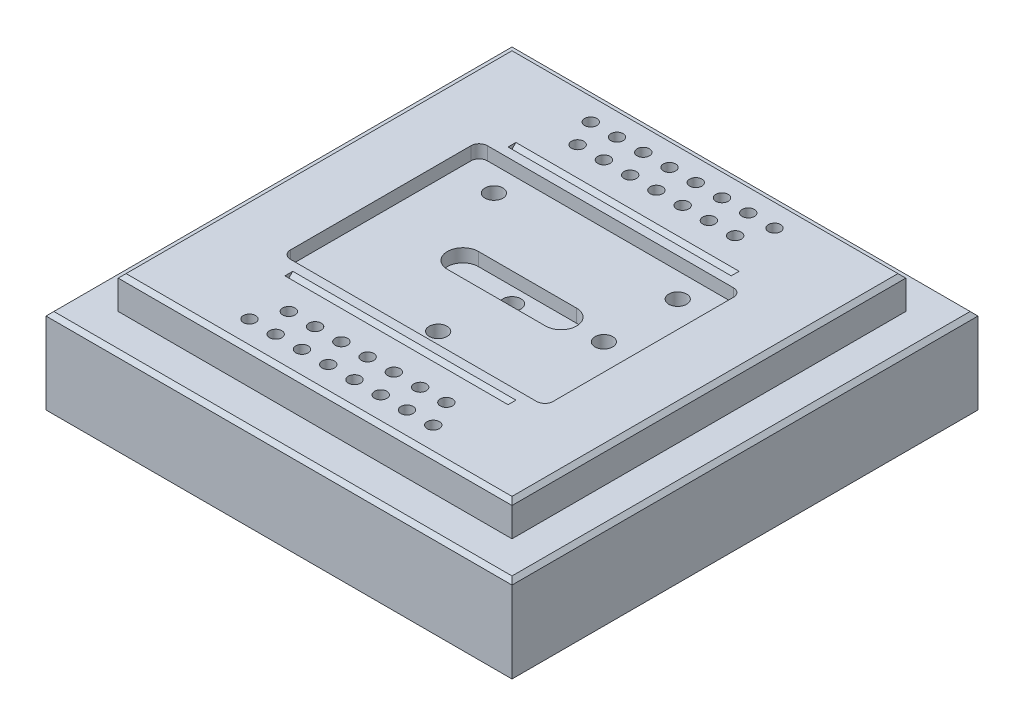
SolidWorks part; units mm, degrees
material "Acrylic (Medium-high impact)"
ref_plane "Front Plane" through (0, 0, 0) normal (0, 0, 1) x (1, 0, 0)
ref_plane "Top Plane" through (0, 0, 0) normal (0, 1, 0) x (1, 0, 0)
ref_plane "Right Plane" through (0, 0, 0) normal (1, 0, 0) x (0, 0, -1)
sketch "Sketch1" plane through (0, 0, 0) normal (0, 1, 0) x (1, 0, 0)
  line L1 (-38.1, 38.1) -> (38.1, 38.1)
  line L2 (-38.1, 38.1) -> (-38.1, -38.1)
  line L3 (-38.1, -38.1) -> (38.1, -38.1)
  line L4 (38.1, 38.1) -> (38.1, -38.1)
  line L5 (-38.1, 38.1) -> (38.1, -38.1) construction
  line L6 (-38.1, -38.1) -> (38.1, 38.1) construction
  point P0 (0, 0)
  dimension "D1" = 76.2
  dimension "D2" = 76.2
extrude "Boss-Extrude1" add sketch "Sketch1" along normal blind 6.35 contours L1 L4 L3 L2
sketch "Sketch13" plane through (0, 0, 0) normal (0, -1, 0) x (1, 0, 0)
  line L1 (-45.085, 45.085) -> (45.085, 45.085)
  line L2 (-45.085, 45.085) -> (-45.085, -45.085)
  line L3 (-45.085, -45.085) -> (45.085, -45.085)
  line L4 (45.085, 45.085) -> (45.085, -45.085)
  line L5 (-45.085, 45.085) -> (45.085, -45.085) construction
  line L6 (-45.085, -45.085) -> (45.085, 45.085) construction
  point P0 (0, 0)
  dimension "D1" = 90.17
  dimension "D2" = 90.17
extrude "Boss-Extrude2" add sketch "Sketch13" along normal blind 16.51
sketch "Sketch2" plane through (0, 6.35, 0) normal (0, 1, 0) x (1, 0, 0)
  line L1 (-23.8125, 19.05) -> (23.8125, 19.05)
  line L2 (-25.4, 17.4625) -> (-25.4, -17.4625)
  line L3 (-23.8125, -19.05) -> (23.8125, -19.05)
  line L4 (25.4, 17.4625) -> (25.4, -17.4625)
  line L5 (-25.4, 19.05) -> (25.4, -19.05) construction
  line L6 (-25.4, -19.05) -> (25.4, 19.05) construction
  arc A0 (-25.4, -17.4625) -> (-23.8125, -19.05) centre (-23.8125, -17.4625) ccw
  arc A1 (23.8125, -19.05) -> (25.4, -17.4625) centre (23.8125, -17.4625) ccw
  arc A2 (23.8125, 19.05) -> (25.4, 17.4625) centre (23.8125, 17.4625) cw
  arc A3 (-23.8125, 19.05) -> (-25.4, 17.4625) centre (-23.8125, 17.4625) ccw
  point P0 (0, 0)
  dimension "D3" = 1.5875
  dimension "D1" = 38.1
  dimension "D2" = 50.8
extrude "Cut-Extrude1" cut sketch "Sketch2" against normal blind 2.54
hole_wizard "3/32 (0.09375) Diameter Hole1" positions "Sketch7" profile "Sketch6" hole size "3/32" standard "ANSI Inch"
sketch "Sketch7" plane through (0, 6.35, 0) normal (0, 1, 0) x (1, 0, 0)
  line L0 (0, 0) -> (0, 38.1) construction
  line L2 (-15.24, 27.94) -> (15.24, 27.94) construction
  line L3 (-38.1, 38.1) -> (38.1, 38.1) construction
  line L4 (-17.78, 33.02) -> (17.78, 33.02) construction
  point P6 (-15.24, 27.94)
  point P7 (15.24, 27.94)
  point P17 (0, 27.94)
  point P18 (-17.78, 33.02)
  point P19 (17.78, 33.02)
  point P30 (-12.7, 33.02)
  point P31 (-7.62, 33.02)
  point P32 (-2.54, 33.02)
  point P33 (2.54, 33.02)
  point P34 (7.62, 33.02)
  point P35 (12.7, 33.02)
  point P36 (17.78, 33.02)
  point P38 (0, 33.02)
  point P53 (-10.16, 27.94)
  point P54 (-5.08, 27.94)
  point P55 (0, 27.94)
  point P56 (5.08, 27.94)
  point P57 (10.16, 27.94)
  point P58 (15.24, 27.94)
  dimension "D1" = 30.48
  dimension "D2" = 5.08
  dimension "D3" = 27.94
  dimension "D4" = 35.56
  dimension "D5" = 8
  dimension "D6" = 7
sketch "Sketch6" plane through (-15.24, 6.35, -27.94) normal (1, 0, 0) x (0, 0, 1)
  line L0 (0, 0) -> (0, 8.3354)
  line L1 (0, 8.3354) -> (1.1906, 7.62)
  line L2 (1.1906, 7.62) -> (1.1906, 0)
  line L5 (1.1906, 0) -> (0, 0)
  line L10 (0, 8.3354) -> (-1.1906, 7.62) construction
  line L11 (0, -6.35) -> (0, 107.95) construction
  dimension "Hole Dia." = 2.3812
  dimension "Hole Depth" = 7.62
  dimension "Drill Angle" = 118
mirror "Mirror1" about plane through (0, 0, 0) normal (0, 0, 1) of "3/32 (0.09375) Diameter Hole1"
sketch "Sketch8" plane through (0, 0, 0) normal (1, 0, 0) x (0, 0, -1)
  line L0 (20.828, 6.35) -> (21.59, 5.588)
  line L1 (-38.1, 6.35) -> (38.1, 6.35) construction
  line L2 (21.59, 5.588) -> (22.352, 6.35)
  line L3 (22.352, 6.35) -> (20.828, 6.35)
  line L4 (21.59, 6.35) -> (21.59, 5.588) construction
  dimension "D1" = 0.762
  dimension "D2" = 21.59
extrude "Cut-Extrude4" cut sketch "Sketch8" against normal mid plane 43.18
mirror "Mirror2" about plane through (0, 0, 0) normal (0, 0, 1) of "Cut-Extrude4"
chamfer "Chamfer1" distance 0.762 angle 45 8 edges at (-38.1, 6.35, 0) (0, 6.35, -38.1) (38.1, 6.35, 0) (0, 6.35, 38.1) (0, 0, -45.085) (-45.085, 0, 0) (0, 0, 45.085) (45.085, 0, 0)
hole_wizard "1/4 (0.25) Diameter Hole1" [suppressed] positions "Sketch10" profile "Sketch11" hole size "1/4" standard "ANSI Inch"
sketch "Sketch10" plane through (0, 6.35, 0) normal (0, 1, 0) x (1, 0, 0)
  line L0 (-31.75, 15.875) -> (-31.75, -15.875) construction
  line L2 (-31.75, 0) -> (0, 0) construction
  line L4 (-38.1, -38.1) -> (-38.1, 38.1) construction
  point P0 (-31.75, 15.875)
  point P2 (-31.75, -15.875)
  dimension "D1" = 31.75
  dimension "D2" = 6.35
sketch "Sketch11" plane through (-31.75, 6.35, -15.875) normal (1, 0, 0) x (0, 0, 1)
  line L0 (0, 0) -> (0, 18.4177)
  line L1 (0, 18.4177) -> (3.175, 16.51)
  line L2 (3.175, 16.51) -> (3.175, 0)
  line L5 (3.175, 0) -> (0, 0)
  line L10 (0, 18.4177) -> (-3.175, 16.51) construction
  line L11 (0, -6.35) -> (0, 107.95) construction
  dimension "Hole Dia." = 6.35
  dimension "Hole Depth" = 16.51
  dimension "Drill Angle" = 118
sketch "Sketch14" plane through (0, -16.51, 0) normal (0, -1, 0) x (1, 0, 0)
  line L0 (-38.735, 34.925) -> (31.115, 34.925)
  line L1 (34.29, 31.75) -> (34.29, -31.75)
  line L2 (31.115, -34.925) -> (-38.735, -34.925)
  line L3 (-41.91, -31.75) -> (-41.91, -15.875)
  line L4 (-38.735, -12.7) -> (-25.4, -12.7)
  line L5 (-22.86, -10.16) -> (-22.86, 10.16)
  line L6 (-25.4, 12.7) -> (-38.735, 12.7)
  line L7 (-41.91, 15.875) -> (-41.91, 31.75)
  line L8 (-22.86, 0) -> (34.29, 0) construction
  line L9 (-45.085, 45.085) -> (-45.085, -45.085) construction
  arc A0 (-41.91, -15.875) -> (-38.735, -12.7) centre (-38.735, -15.875) cw
  arc A1 (-38.735, -34.925) -> (-41.91, -31.75) centre (-38.735, -31.75) cw
  arc A2 (34.29, -31.75) -> (31.115, -34.925) centre (31.115, -31.75) cw
  arc A3 (31.115, 34.925) -> (34.29, 31.75) centre (31.115, 31.75) cw
  arc A4 (-38.735, 12.7) -> (-41.91, 15.875) centre (-38.735, 15.875) cw
  arc A5 (-38.735, 34.925) -> (-41.91, 31.75) centre (-38.735, 31.75) ccw
  arc A6 (-25.4, -12.7) -> (-22.86, -10.16) centre (-25.4, -10.16) ccw
  arc A7 (-22.86, 10.16) -> (-25.4, 12.7) centre (-25.4, 10.16) ccw
  point P15 (-22.86, -12.7)
  point P22 (34.29, -34.925)
  point P25 (34.29, 34.925)
  point P28 (-41.91, 12.7)
  point P31 (-41.91, 34.925)
  point P34 (-22.86, 12.7)
  dimension "D6" = 3.175
  dimension "D7" = 2.54
  dimension "D1" = 69.85
  dimension "D2" = 3.175
  dimension "D3" = 19.05
  dimension "D4" = 76.2
  dimension "D5" = 25.4
extrude "Cut-Extrude8" cut sketch "Sketch14" against normal blind 13.97
sketch "Sketch15" plane through (-45.085, 0, 0) normal (-1, 0, 0) x (0, 0, 1)
  line L0 (-23.8125, -8.89) -> (-23.8125, -2.54) construction
  line L1 (-15.875, -2.54) -> (-31.75, -2.54) construction
  line L2 (23.8125, -8.89) -> (23.8125, -2.54) construction
  line L3 (31.75, -2.54) -> (15.875, -2.54) construction
  line L4 (45.085, -16.51) -> (-45.085, -16.51) construction
  circle A0 centre (-23.8125, -8.89) radius 4.7625
  circle A1 centre (23.8125, -8.89) radius 4.7625
  point P7 (-23.8125, -2.54)
  point P11 (23.8125, -2.54)
  dimension "D1" = 9.525
  dimension "D2" = 7.62
extrude "Cut-Extrude9" cut sketch "Sketch15" against normal blind 5.08
hole_wizard "#8-32 Tapped Hole1" positions "Sketch21" profile "Sketch22" tap size "#8-32" standard "ANSI Inch"
sketch "Sketch21" plane through (0, 3.81, 0) normal (0, 1, 0) x (1, 0, 0)
  line L0 (-17.78, 14.2875) -> (17.78, 14.2875) construction
  line L2 (0, -14.2875) -> (0, 14.2875) construction
  point P0 (-17.78, 14.2875)
  point P2 (17.78, 14.2875)
  point P4 (0, -14.2875)
  point P16 (0, 14.2875)
  point P19 (0, 0)
  point P20 (17.78, 0)
  dimension "D1" = 35.56
  dimension "D2" = 28.575
sketch "Sketch22" plane through (-17.78, 3.81, -14.2875) normal (1, 0, 0) x (0, 0, 1)
  line L0 (0, 0) -> (0, 11.7566)
  line L1 (0, 11.7566) -> (1.7272, 10.7188)
  line L2 (1.7272, 10.7188) -> (1.7272, 0)
  line L5 (1.7272, 0) -> (0, 0)
  line L10 (0, 11.7566) -> (-1.7272, 10.7188) construction
  line L11 (0, -6.35) -> (0, 107.95) construction
  dimension "Tap Drill Dia." = 3.4544
  dimension "Tap Drill Depth" = 10.7188
  dimension "Drill Angle" = 118
cosmetic thread "Hole Thread1" parameters "D1"=6.35, "D2"=4.1656
cosmetic thread "Hole Thread2" parameters "D1"=6.35, "D2"=4.1656
cosmetic thread "Hole Thread3" parameters "D1"=6.35, "D2"=4.1656
cosmetic thread "Hole Thread4" parameters "D1"=6.35, "D2"=4.1656
cosmetic thread "Hole Thread5" parameters "D1"=6.35, "D2"=4.1656
sketch "Sketch23" plane through (0, 3.81, 0) normal (0, 1, 0) x (1, 0, 0)
  line L0 (-9.5, 0) -> (9.5, 0) construction
  line L1 (-9.5, 3) -> (9.5, 3)
  line L2 (-9.5, -3) -> (9.5, -3)
  arc A0 (-9.5, 3) -> (-9.5, -3) centre (-9.5, 0) ccw
  arc A1 (9.5, -3) -> (9.5, 3) centre (9.5, 0) ccw
  point P2 (0, 0)
  dimension "D2" = 25
  dimension "D1" = 6
extrude "Cut-Extrude17" cut sketch "Sketch23" against normal blind 2.54
sketch "Sketch16" [suppressed] plane through (0, 6.35, 0) normal (0, 1, 0) x (1, 0, 0)
  line L0 (27.5188, -32.9462) -> (27.5188, -23.6203) construction
  line L1 (27.0539, 0) -> (29.5939, 0) construction
  line L2 (29.5939, 3.81) -> (29.5939, -3.81) construction
  line L3 (30.8639, 2.54) -> (30.8639, -2.54) construction
  line L4 (32.1339, 1.27) -> (32.1339, -1.27) construction
  line L5 (25.4, -15.875) -> (25.4, 15.875) construction
  line L6 (29.5939, 3.81) -> (29.5939, -3.81) construction
  line L7 (29.8479, 3.81) -> (29.8479, -3.81)
  line L8 (29.3399, 3.81) -> (29.3399, 0.254)
  line L9 (30.8639, 2.54) -> (30.8639, -2.54) construction
  line L10 (31.1179, 2.54) -> (31.1179, -2.54)
  line L11 (30.6099, 2.54) -> (30.6099, -2.54)
  line L12 (32.1339, 1.27) -> (32.1339, -1.27) construction
  line L13 (32.3879, 1.27) -> (32.3879, -1.27)
  line L14 (31.8799, 1.27) -> (31.8799, -1.27)
  line L15 (27.0539, 0) -> (29.5939, 0) construction
  line L16 (27.0539, 0.254) -> (29.3399, 0.254)
  line L17 (27.0539, -0.254) -> (29.3399, -0.254)
  line L18 (29.3399, -0.254) -> (29.3399, -3.81)
  arc A0 (29.8479, 3.81) -> (29.3399, 3.81) centre (29.5939, 3.81) ccw
  arc A1 (29.3399, -3.81) -> (29.8479, -3.81) centre (29.5939, -3.81) ccw
  arc A2 (31.1179, 2.54) -> (30.6099, 2.54) centre (30.8639, 2.54) ccw
  arc A3 (30.6099, -2.54) -> (31.1179, -2.54) centre (30.8639, -2.54) ccw
  arc A4 (32.3879, 1.27) -> (31.8799, 1.27) centre (32.1339, 1.27) ccw
  arc A5 (31.8799, -1.27) -> (32.3879, -1.27) centre (32.1339, -1.27) ccw
  arc A6 (27.0539, 0.254) -> (27.0539, -0.254) centre (27.0539, 0) ccw
  text T0 "+HV"
  point P7 (29.5939, 0)
  point P8 (29.5939, 0)
  point P11 (30.8639, 0)
  point P14 (32.1339, 0)
  point P18 (25.4, 0)
  point P22 (30.8639, 0)
  point P27 (32.1339, 0)
  point P32 (28.3239, 0)
  dimension "D1" = 1.27
  dimension "D2" = 1.27
  dimension "D3" = 7.62
  dimension "D4" = 5.08
  dimension "D5" = 2.54
  dimension "D6" = 2.54
  dimension "D7" = 0.508
  dimension "D8" = 0.508
  dimension "D9" = 0.508
  dimension "D10" = 0.508
extrude "Cut-Extrude10" [suppressed] cut sketch "Sketch16" against normal blind 1.27
sketch "Sketch17" [suppressed] plane through (-45.085, 0, 0) normal (-1, 0, 0) x (0, 0, 1)
  line L0 (-42.545, -7.62) -> (-34.925, -7.62) construction
  line L1 (32.385, -7.62) -> (42.545, -7.62) construction
  line L2 (-45.085, -16.51) -> (-45.085, -0.762) construction
  line L3 (45.085, -16.51) -> (45.085, -0.762) construction
  line L4 (45.085, -16.51) -> (-45.085, -16.51) construction
  line L5 (-7.9214, -5.1188) -> (7.9214, -5.1188) construction
  line L6 (-7.9214, -13.5925) -> (7.9214, -13.5925) construction
  line L7 (0, -13.5925) -> (0, -5.1188) construction
  line L8 (-5.4331, -9.3556) -> (5.4331, -9.3556) construction
  line L10 (-44.323, 0) -> (44.323, 0) construction
  text T0 "+HV"
  text T1 "SIG"
  text T2 "06/16" font "Century Gothic" height in points 10
  text T3 "03/17" font "Century Gothic" height in points 10
  text T4 "to" font "Century Gothic" height in points 10
  point P8 (-38.735, -7.62)
  point P15 (0, -5.1188)
  point P16 (6.8453, -6.4638)
  point P18 (0, 0)
  point P24 (0, -9.3556)
  point P25 (1.398, -10.1626)
  point P28 (0, 0)
  point P29 (5.4331, -9.3556)
  point P30 (7.9214, -13.5925)
  dimension "D1" = 2.54
  dimension "D2" = 2.54
  dimension "D3" = 10.16
  dimension "D4" = 7.62
  dimension "D5" = 8.89
extrude "Cut-Extrude11" [suppressed] cut sketch "Sketch17" against normal blind 0.635
sketch "Sketch18" [suppressed] plane through (45.085, 0, 0) normal (1, 0, 0) x (0, 0, -1)
  line L0 (-44.323, 0) -> (44.323, 0) construction
  line L1 (-31.0621, -13.9056) -> (31.0621, -13.9056) construction
  line L2 (-32.4405, -3.5632) -> (32.4405, -3.5632) construction
  line L3 (-32.4405, -3.5632) -> (-32.4405, -8.6432) construction
  line L4 (-32.4405, -8.6432) -> (32.4405, -8.6432) construction
  line L5 (32.4405, -3.5632) -> (32.4405, -8.6432) construction
  line L6 (-32.4405, -3.5632) -> (32.4405, -8.6432) construction
  line L7 (-32.4405, -8.6432) -> (32.4405, -3.5632) construction
  text T0 "Alpha Detector" font "Century Gothic" height 5.08
  text T1 "KSU Nuclear Engineering" font "Century Gothic" height in points 10
  point P0 (0, -6.1032)
  point P3 (0, -13.9056)
  point P11 (0, 0)
  point P13 (-31.0621, -13.9056)
  dimension "D1" = 5.08
extrude "Cut-Extrude13" [suppressed] cut sketch "Sketch18" against normal blind 0.635
sketch "Sketch19" [suppressed] plane through (0, 0, 45.085) normal (0, 0, 1) x (1, 0, 0)
  line L0 (0, 0) -> (0, -16.51) construction
  line L1 (-38.1, -1.9558) -> (38.1, -1.9558) construction
  line L2 (-38.1, -1.9558) -> (-38.1, -12.1158) construction
  line L3 (-38.1, -12.1158) -> (0, -12.1158) construction
  line L4 (38.1, -1.9558) -> (38.1, -12.1158) construction
  line L5 (-38.1, -1.9558) -> (38.1, -12.1158) construction
  line L6 (-38.1, -12.1158) -> (38.1, -1.9558) construction
  line L7 (-44.323, 0) -> (44.323, 0) construction
  line L8 (45.085, -16.51) -> (-45.085, -16.51) construction
  line L9 (-38.1, -7.0358) -> (0, -7.0358) construction
  line L10 (0, -7.0358) -> (38.1, -7.0358) construction
  line L11 (0, -12.1158) -> (38.1, -12.1158) construction
  text T0 "Andrew Jones" font "Century Gothic" height in points 10
  text T1 "Shawn Sinclair" font "Century Gothic" height in points 10
  text T2 "Kurt Jacobson" font "Century Gothic" height in points 10
  text T3 "Christina Kirby" font "Century Gothic" height in points 10
  point P0 (0, -7.0358)
  point P14 (36.9016, 22.6235)
  point P16 (0, 0)
  point P17 (0, -13.335)
  point P22 (0, 0)
  dimension "D1" = 10.16
  dimension "D2" = 76.2
  dimension "D3" = 9.4742
extrude "Cut-Extrude14" [suppressed] cut sketch "Sketch19" against normal blind 0.635
sketch "Sketch20" [suppressed] plane through (0, 0, -45.085) normal (0, 0, -1) x (-1, 0, 0)
  line L0 (0, 0) -> (0, -16.51) construction
  line L1 (-36.5038, -1.9558) -> (36.5038, -1.9558) construction
  line L2 (-36.5038, -1.9558) -> (-36.5038, -12.1158) construction
  line L3 (-36.5038, -12.1158) -> (36.5038, -12.1158) construction
  line L4 (36.5038, -1.9558) -> (36.5038, -12.1158) construction
  line L5 (-36.5038, -1.9558) -> (36.5038, -12.1158) construction
  line L6 (-36.5038, -12.1158) -> (36.5038, -1.9558) construction
  line L7 (-44.323, 0) -> (44.323, 0) construction
  line L8 (45.085, -16.51) -> (-45.085, -16.51) construction
  line L9 (-36.5038, -7.0358) -> (36.5038, -7.0358) construction
  line L10 (0, -7.0358) -> (-38.1, -7.0358) construction
  text T0 "Dr. Eduardo B. Farfan" font "Century Gothic" height in points 10
  text T1 "Dr. Sandip Das" font "Century Gothic" height in points 10
  point P0 (0, -7.0358)
  dimension "D1" = 10.16
extrude "Cut-Extrude15" [suppressed] cut sketch "Sketch20" against normal blind 0.635
